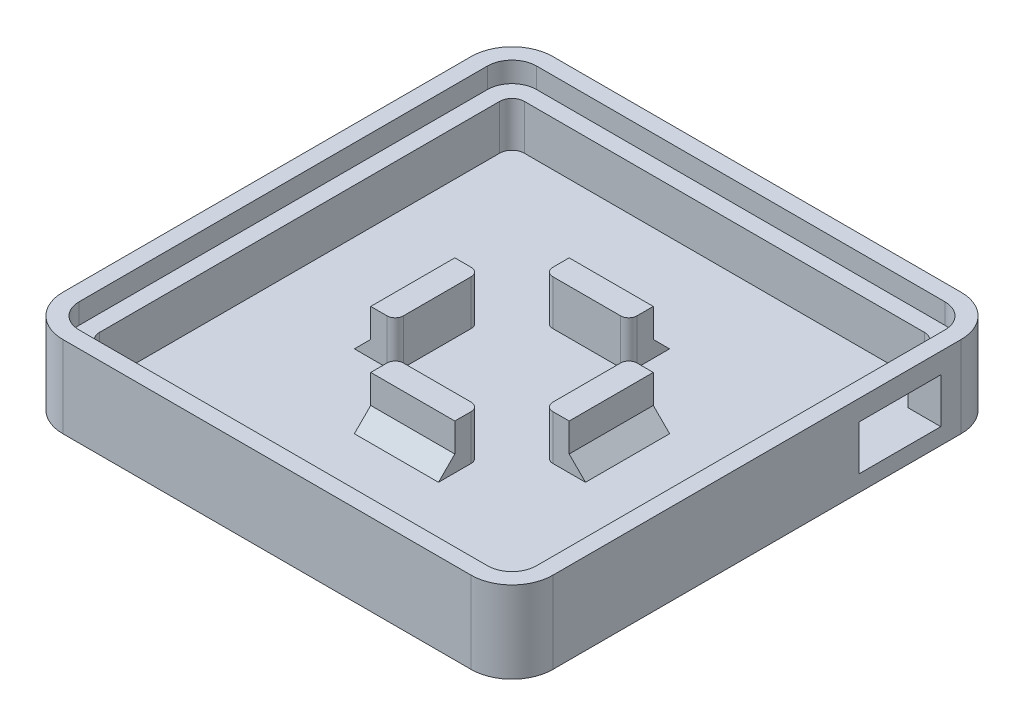
SolidWorks part; units mm, degrees
ref_plane "Plano frontal" through (0, 0, 0) normal (0, 0, 1) x (1, 0, 0)
ref_plane "Plano superior" through (0, 0, 0) normal (0, 1, 0) x (1, 0, 0)
ref_plane "Plano direito" through (0, 0, 0) normal (1, 0, 0) x (0, 0, -1)
sketch "Esboço1" plane through (0, 0, 0) normal (0, 1, 0) x (1, 0, 0)
  line L1 (-30, 30) -> (30, 30)
  line L2 (-30, 30) -> (-30, -30)
  line L3 (-30, -30) -> (30, -30)
  line L4 (30, 30) -> (30, -30)
  line L5 (-30, 30) -> (30, -30) construction
  line L6 (-30, -30) -> (30, 30) construction
  point P0 (0, 0)
  dimension "D1" = 60
  dimension "D2" = 60
extrude "Base" add sketch "Esboço1" along normal blind 2
sketch "Esboço3" plane through (0, 2, 0) normal (0, 1, 0) x (1, 0, 0)
  line L0 (-12.15, 12.15) -> (12.15, 12.15)
  line L1 (-9.15, 9.15) -> (9.15, 9.15)
  line L2 (-9.15, 9.15) -> (-9.15, -9.15)
  line L3 (-9.15, -9.15) -> (9.15, -9.15)
  line L4 (9.15, 9.15) -> (9.15, -9.15)
  line L5 (-9.15, 9.15) -> (9.15, -9.15) construction
  line L6 (-9.15, -9.15) -> (9.15, 9.15) construction
  line L7 (12.15, 12.15) -> (12.15, -12.15)
  line L8 (-12.15, -12.15) -> (12.15, -12.15)
  line L9 (-12.15, 12.15) -> (-12.15, -12.15)
  point P0 (0, 0)
  dimension "D1" = 18.3
  dimension "D2" = 18.3
  dimension "D3" = 3
extrude "Encaixes da Arvore" add sketch "Esboço3" along normal blind 5.5
sketch "Esboço4" plane through (0, 2, 0) normal (0, 1, 0) x (1, 0, 0)
  line L0 (-26, 26) -> (-26, -26)
  line L1 (-30, 30) -> (30, 30)
  line L2 (-30, 30) -> (-30, -30)
  line L3 (-30, -30) -> (30, -30)
  line L4 (30, 30) -> (30, -30)
  line L5 (-30, 30) -> (30, -30) construction
  line L6 (-30, -30) -> (30, 30) construction
  line L7 (-26, -26) -> (26, -26)
  line L8 (26, 26) -> (26, -26)
  line L9 (-26, 26) -> (26, 26)
  point P0 (0, 0)
  dimension "D1" = 4
extrude "Paredes" add sketch "Esboço4" along normal blind 8
sketch "Esboço5" plane through (0, 7.5, 0) normal (0, 1, 0) x (1, 0, 0)
  line L0 (0, 15.7353) -> (0, -14.3539) construction
  line L1 (-14.0363, 0) -> (14.8621, 0) construction
  line L2 (12.15, 5.15) -> (5.15, 5.15)
  line L3 (-12.15, 12.15) -> (-5.15, 12.15)
  line L4 (-12.15, 12.15) -> (-12.15, 5.15)
  line L5 (-12.15, 5.15) -> (-5.15, 5.15)
  line L6 (-5.15, 12.15) -> (-5.15, 5.15)
  line L7 (12.15, 12.15) -> (12.15, 5.15)
  line L8 (12.15, 12.15) -> (5.15, 12.15)
  line L9 (5.15, 12.15) -> (5.15, 5.15)
  line L10 (5.15, -12.15) -> (5.15, -5.15)
  line L11 (12.15, -12.15) -> (5.15, -12.15)
  line L12 (12.15, -12.15) -> (12.15, -5.15)
  line L13 (12.15, -5.15) -> (5.15, -5.15)
  line L14 (-12.15, -5.15) -> (-5.15, -5.15)
  line L15 (-12.15, -12.15) -> (-12.15, -5.15)
  line L16 (-12.15, -12.15) -> (-5.15, -12.15)
  line L17 (-5.15, -12.15) -> (-5.15, -5.15)
  point P25 (0, 0)
  dimension "D1" = 7
  dimension "D2" = 7
  dimension "D3" = 4
extrude "Corte dos Encaixe" cut sketch "Esboço5" against normal up to surface (5.5 mm away) up to face at (0, 2, 0)
sketch "Esboço6" plane through (0, 10, 0) normal (0, 1, 0) x (1, 0, 0)
  line L0 (-28, 28) -> (28, 28)
  line L1 (-26, -26) -> (26, -26)
  line L2 (-26, -26) -> (-26, 26)
  line L3 (-26, 26) -> (26, 26)
  line L4 (26, -26) -> (26, 26)
  line L5 (-26, -26) -> (26, 26) construction
  line L6 (-26, 26) -> (26, -26) construction
  line L7 (28, -28) -> (28, 28)
  line L8 (-28, -28) -> (28, -28)
  line L9 (-28, -28) -> (-28, 28)
  point P0 (0, 0)
  dimension "D1" = 52
  dimension "D2" = 52
  dimension "D3" = 2
extrude "Corte-extrusão2" cut sketch "Esboço6" against normal blind 2.5
fillet "Filete5" radius 1.5 4 edges at (26, 4.75, 26) (-26, 4.75, 26) (26, 4.75, -26) (-26, 4.75, -26)
fillet "Filete6" radius 3 4 edges at (-28, 8.75, -28) (-28, 8.75, 28) (28, 8.75, 28) (28, 8.75, -28)
sketch "Esboço7" plane through (26, 0, 0) normal (-1, 0, 0) x (0, 0, 1)
  line L0 (24.5, 2) -> (-24.5, 2) construction
  line L1 (-22.5, 2) -> (-12.5, 2)
  line L2 (-22.5, 2) -> (-22.5, 7.5)
  line L3 (-22.5, 7.5) -> (-12.5, 7.5)
  line L4 (-12.5, 2) -> (-12.5, 7.5)
  line L5 (-24.5, 7.5) -> (-24.5, 2) construction
  dimension "D1" = 10
  dimension "D2" = 5.5
  dimension "D3" = 2
extrude "Corte-extrusão3" cut sketch "Esboço7" against normal through all
chamfer "Chanfro2" distance 2 angle 45 4 edges at (-12.15, 2, 0) (0, 2, 12.15) (12.15, 2, 0) (0, 2, -12.15)
fillet "Filete19" radius 1 8 edges at (-9.15, 4.75, -5.15) (-9.15, 4.75, 5.15) (-5.15, 4.75, 9.15) (5.15, 4.75, 9.15) (9.15, 4.75, 5.15) (9.15, 4.75, -5.15) (5.15, 4.75, -9.15) (-5.15, 4.75, -9.15)
fillet "Filete20" radius 5 4 edges at (30, 5, 30) (30, 5, -30) (-30, 5, -30) (-30, 5, 30)
